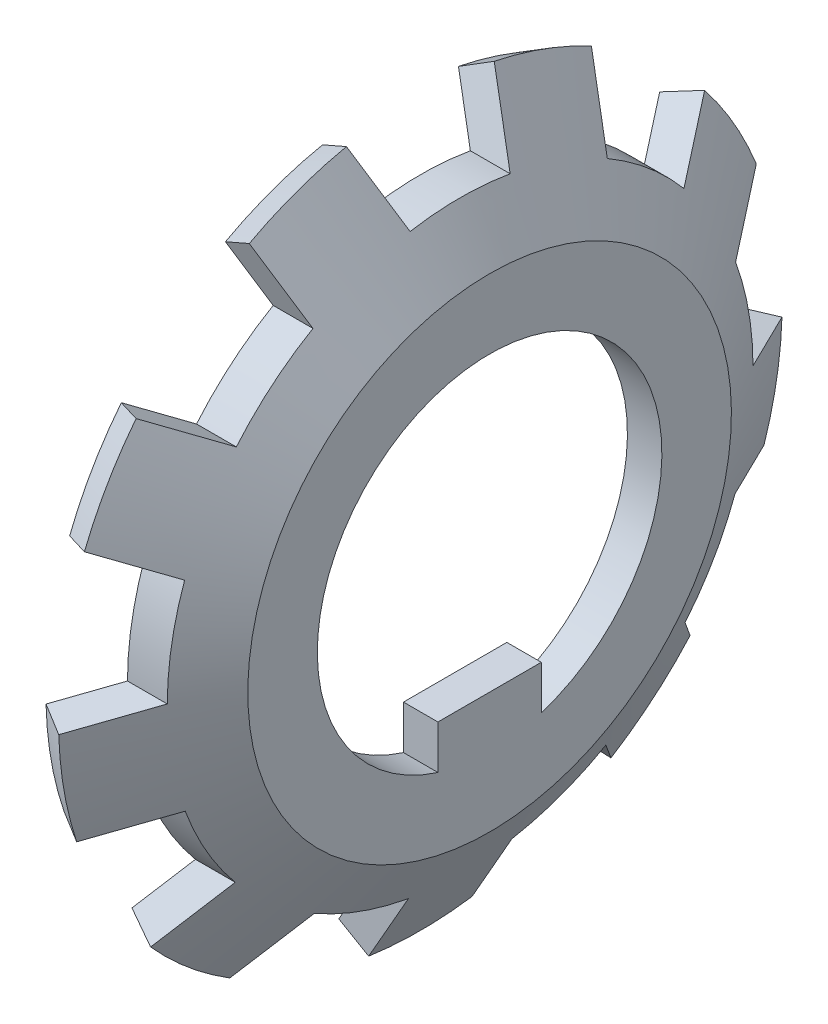
SolidWorks part; units mm, degrees
ref_plane "Přední rovina" through (0, 0, 0) normal (0, 0, 1) x (1, 0, 0)
ref_plane "Vrchní rovina" through (0, 0, 0) normal (0, 1, 0) x (1, 0, 0)
ref_plane "Pravá rovina" through (0, 0, 0) normal (1, 0, 0) x (0, 0, -1)
sketch "Skica1" plane through (0, 0, 0) normal (0, 0, 1) x (1, 0, 0)
  line L0 (0, 0) -> (0, 6.75)
  line L1 (0, 6.75) -> (-1.8764, 10)
  line L2 (-1.8764, 10) -> (-1.0104, 10.5)
  line L3 (-1.0104, 10.5) -> (1, 7.0179)
  line L4 (1, 7.0179) -> (1, 0)
  line L5 (1, 0) -> (0, 0)
  line L6 (0, 0) -> (-1.8764, 0) construction
  dimension "D1" = 13.5
  dimension "D2" = 30
  dimension "D3" = 21
  dimension "D4" = 1
revolve "Otočit kolem osy1" add sketch "Skica1" angle 360 about L6
sketch "Skica2" plane through (1, 0, 0) normal (1, 0, 0) x (0, 0, -1)
  line L0 (1.5, -4.7697) -> (1.5, -3.5)
  line L1 (1.5, -3.5) -> (-1.5, -3.5)
  line L2 (-1.5, -3.5) -> (-1.5, -4.7697)
  line L3 (0, 0) -> (0, -3.5) construction
  arc A0 (1.5, -4.7697) -> (-1.5, -4.7697) centre (0, 0) ccw
  dimension "D3" = 10
  dimension "D1" = 3
  dimension "D2" = 8.5
extrude "Odebrat vysunutím1" cut sketch "Skica2" against normal up to next
sketch "Skica3" plane through (1, 0, 0) normal (1, 0, 0) x (0, 0, -1)
  line L0 (0, 0) -> (0, -10.5) construction
  line L1 (-1.5, -10.3923) -> (-1.5, -8.3666)
  line L2 (0, 0) -> (-6.7493, -8.0435) construction
  line L3 (-5.531, -8.9251) -> (-4.2289, -7.3734)
  circle A0 centre (0, 0) radius 10.5 construction
  arc A1 (-4.2289, -7.3734) -> (-1.5, -8.3666) centre (0, 0) ccw
  arc A2 (-5.531, -8.9251) -> (-1.5, -10.3923) centre (0, 0) ccw
  dimension "D4" = 2
  dimension "D1" = 40
  dimension "f2" = 3
extrude "Odebrat vysunutím2" cut sketch "Skica3" against normal up to next
pattern_circular "Kruhové pole1" count 9 over 360 about axis through (0, 0, 0) along (1, 0, 0) of "Odebrat vysunutím2"
equation "\"D1@Skica3\" = 360/\"D1@Kruhové pole1\""
